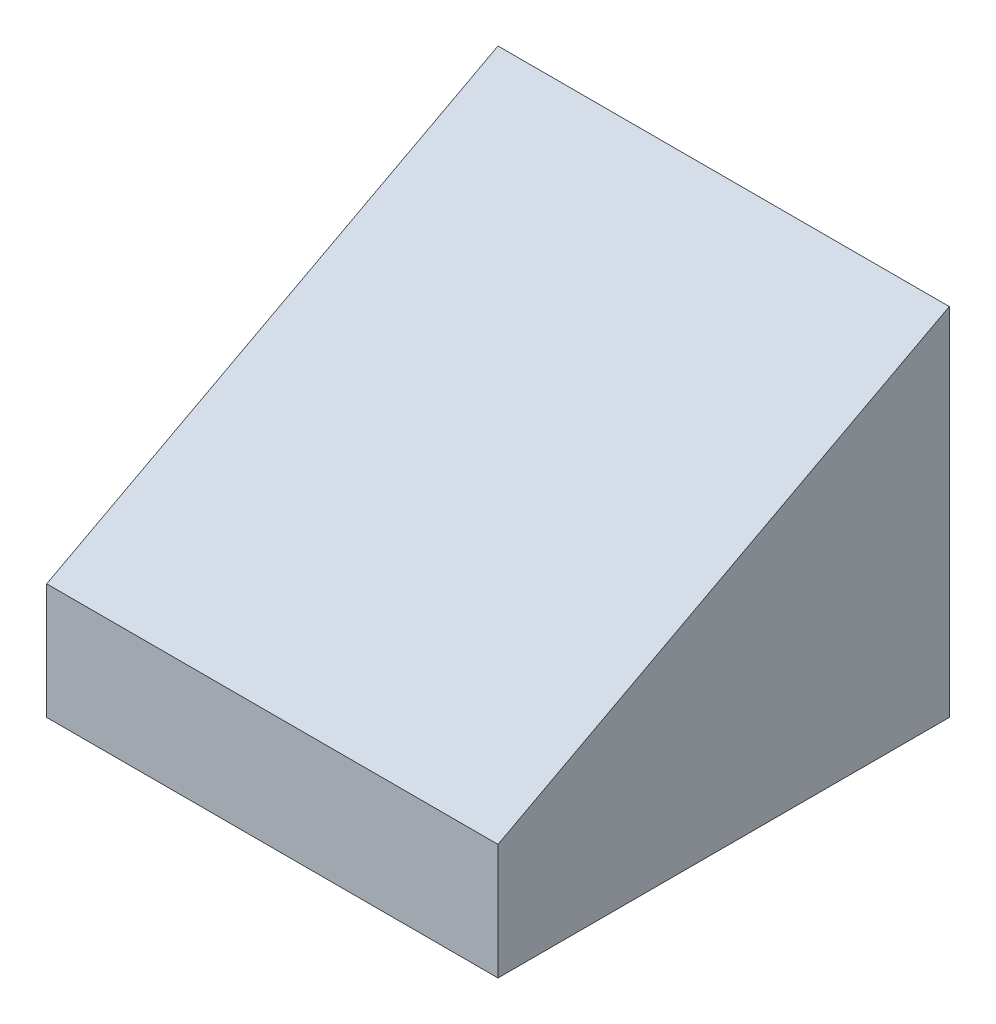
SolidWorks part; units mm, degrees
ref_plane "Front Plane" through (0, 0, 0) normal (0, 0, 1) x (1, 0, 0)
ref_plane "Top Plane" through (0, 0, 0) normal (0, 1, 0) x (1, 0, 0)
ref_plane "Right Plane" through (0, 0, 0) normal (1, 0, 0) x (0, 0, -1)
sketch "Sketch1" plane through (0, 0, 0) normal (1, 0, 0) x (0, 0, -1)
  line L0 (0, 0) -> (-7.8, 0)
  line L1 (-7.8, 0) -> (-7.8, 2)
  line L2 (-7.8, 2) -> (0, 6.15)
  line L3 (0, 6.15) -> (0, 0)
  dimension "D1" = 6.15
  dimension "D2" = 7.8
  dimension "D3" = 2
extrude "Boss-Extrude1" add sketch "Sketch1" against normal blind 7.8
shell "Shell1" thickness 1.5
